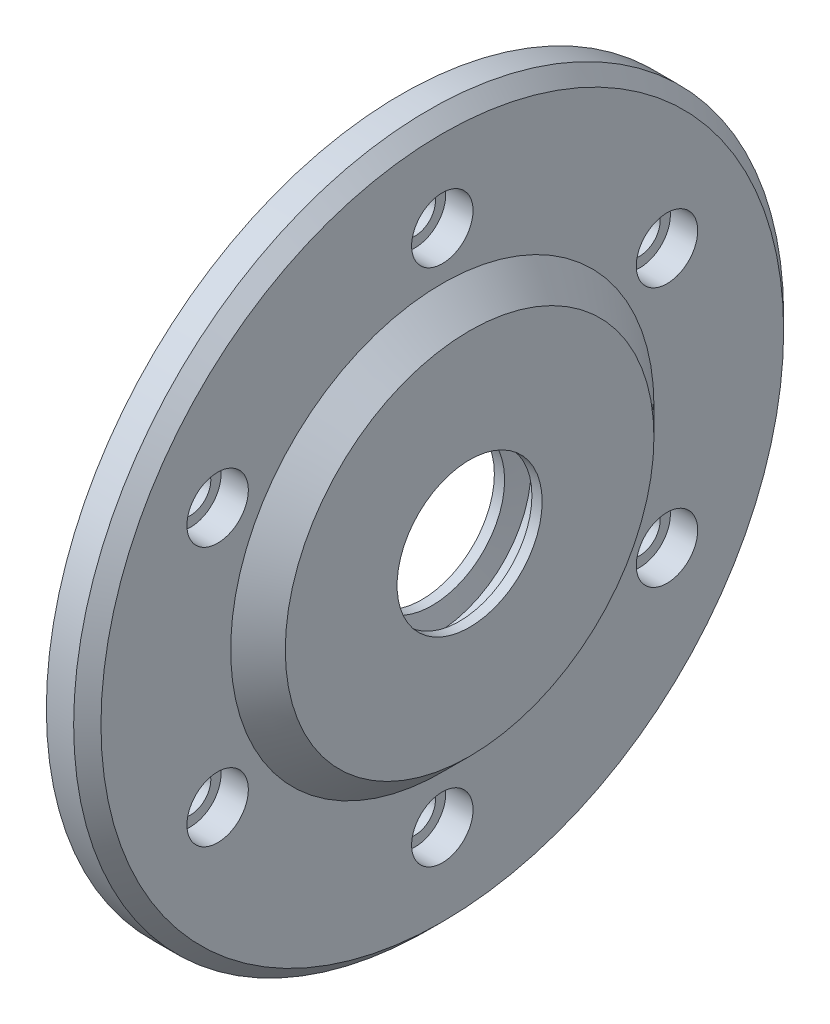
SolidWorks part; units mm, degrees
material "Серое литое железо"
ref_plane "Спереди" through (0, 0, 0) normal (0, 0, 1) x (1, 0, 0)
ref_plane "Сверху" through (0, 0, 0) normal (0, 1, 0) x (1, 0, 0)
ref_plane "Справа" through (0, 0, 0) normal (1, 0, 0) x (0, 0, -1)
sketch "Эскиз1" plane through (0, 0, 0) normal (0, 0, 1) x (1, 0, 0)
  line L0 (0, 52) -> (0, 0)
  line L1 (0, 0) -> (6, 0)
  line L2 (6, 0) -> (6, 52)
  line L3 (6, 52) -> (0, 52)
  line L4 (0, 0) -> (6, 0) construction
revolve "Повернуть1" add sketch "Эскиз1" angle 360 about L4
sketch "Эскиз2" plane through (6, 0, 0) normal (1, 0, 0) x (0, 0, -1)
  circle A0 centre (0, 0) radius 31
extrude "Бобышка-Вытянуть1" add sketch "Эскиз2" along normal blind 4 draft 45
sketch "Эскиз3" plane through (0, 0, 0) normal (-1, 0, 0) x (0, 0, 1)
  circle A0 centre (0, 0) radius 33
extrude "Бобышка-Вытянуть2" add sketch "Эскиз3" along normal blind 1
sketch "Эскиз4" plane through (0, 0, 0) normal (0, 0, 1) x (1, 0, 0)
  line L0 (-1, 25) -> (-1, 0)
  line L1 (-1, 0) -> (10, 0)
  line L2 (10, 0) -> (10, 10.6264)
  line L3 (10, 10.6264) -> (8.5, 10.6264)
  line L4 (8.5, 10.6264) -> (8, 14)
  line L5 (8, 14) -> (5, 14)
  line L6 (5, 14) -> (4.5, 10.6264)
  line L7 (4.5, 10.6264) -> (3, 10.6264)
  line L8 (3, 10.6264) -> (3, 18)
  line L9 (3, 18) -> (0, 18)
  line L10 (0, 18) -> (0, 25)
  line L11 (0, 25) -> (-1, 25)
  line L12 (-1, 0) -> (10, 0) construction
revolve "Вырез-Повернуть1" cut sketch "Эскиз4" angle 360 about L12
hole_wizard "Отверстие1" positions "Эскиз6" profile "Эскиз5" legacy
sketch "Эскиз6" plane through (6, 0, 0) normal (1, 0, 0) x (0, 0, -1)
  point P0 (32.909, -19)
  point P1 (0, -38)
  point P2 (-32.909, -19)
  point P3 (-32.909, 19)
  point P4 (0, 38)
  point P5 (32.909, 19)
sketch "Эскиз5" plane through (6, -19, -32.909) normal (0, 1, 0) x (0, 0, -1)
  line L0 (0, 0) -> (0, 7)
  line L1 (0, 7) -> (3, 7)
  line L2 (3, 7) -> (3, 4)
  line L3 (3, 4) -> (4.5, 4)
  line L4 (4.5, 4) -> (4.5, 0)
  line L5 (4.5, 0) -> (0, 0)
  line L6 (0, 110) -> (0, -10) construction
  dimension "Диаметр" = 6
  dimension "Глубина" = 7
  dimension "Диа. цековки" = 9
  dimension "Глуб. цековки" = 4
chamfer "Фаска1" distance 2 angle 45 1 edges at (6, 0, -52)
